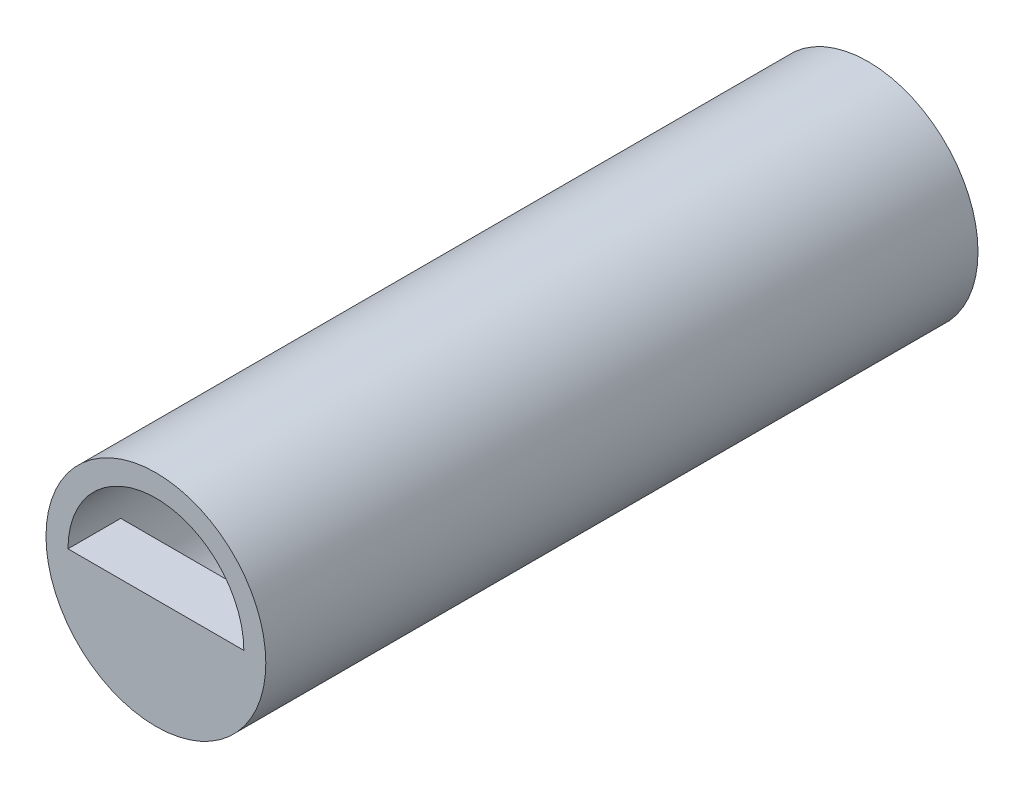
SolidWorks part; units mm, degrees
ref_plane "Alzado" through (0, 0, 0) normal (0, 0, 1) x (1, 0, 0)
ref_plane "Planta" through (0, 0, 0) normal (0, 1, 0) x (1, 0, 0)
ref_plane "Vista lateral" through (0, 0, 0) normal (1, 0, 0) x (0, 0, -1)
sketch "Croquis1" plane through (0, 0, 0) normal (0, 0, 1) x (1, 0, 0)
  circle A0 centre (0, 0) radius 2.5
  circle A1 centre (0, 0) radius 2
  dimension "D1" = 4
  dimension "D2" = 5
extrude "Saliente-Extruir1" add sketch "Croquis1" along normal blind 15
sketch "Croquis2" plane through (0, 0, 15) normal (0, 0, 1) x (1, 0, 0)
  circle A1 centre (0, 0) radius 2.5
extrude "Saliente-Extruir2" add sketch "Croquis2" along normal blind 1.2
sketch "Croquis3" plane through (0, 0, 16.2) normal (0, 0, 1) x (1, 0, 0)
  line L0 (2, 0) -> (-2, 0)
  arc A2 (2, 0) -> (-2, 0) centre (0, 0) ccw
  dimension "D1" = 4
extrude "Cortar-Extruir1" cut sketch "Croquis3" against normal blind 1.2
